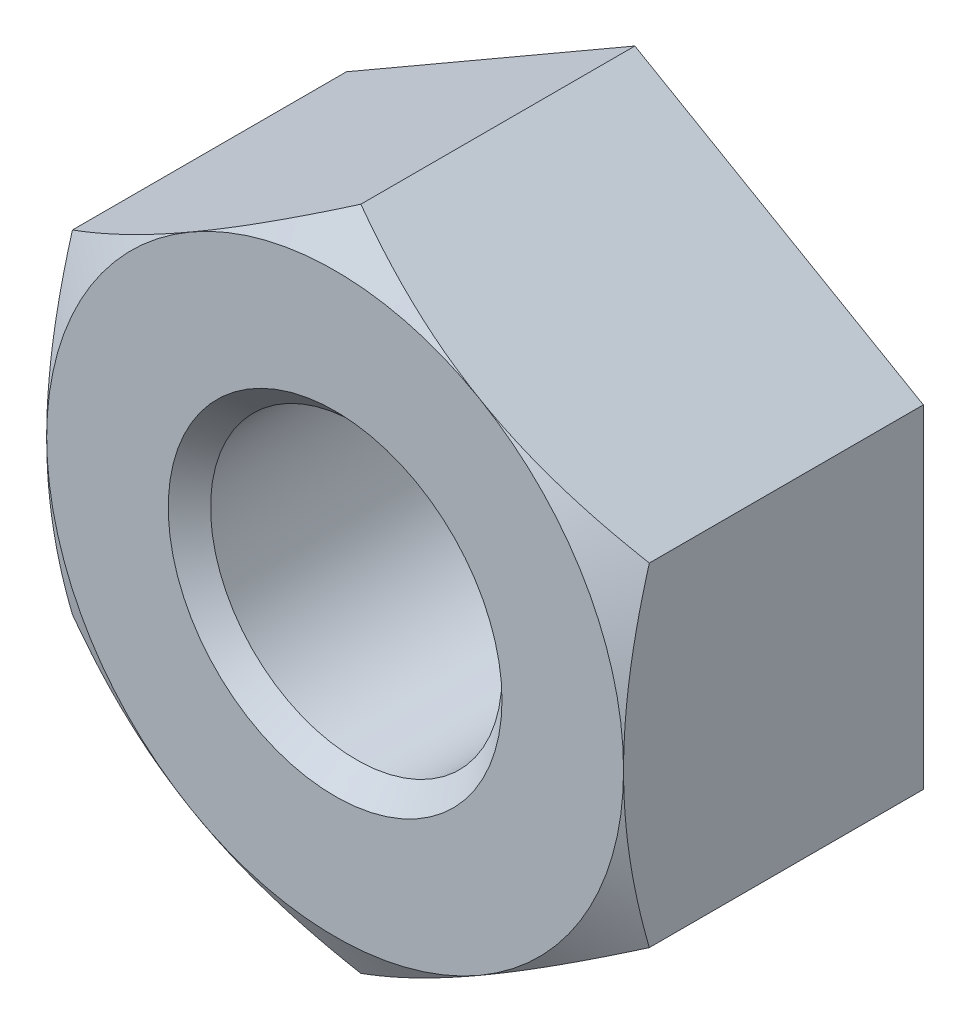
SolidWorks part; units mm, degrees
ref_plane "Front Plane" through (0, 0, 0) normal (0, 0, 1) x (1, 0, 0)
ref_plane "Top Plane" through (0, 0, 0) normal (0, 1, 0) x (1, 0, 0)
ref_plane "Right Plane" through (0, 0, 0) normal (1, 0, 0) x (0, 0, -1)
sketch "Sketch1" plane through (0, 0, 0) normal (0, 0, 1) x (1, 0, 0)
  line L1 (20.7846, -12) -> (20.7846, 12)
  line L2 (20.7846, 12) -> (0, 24)
  line L3 (0, 24) -> (-20.7846, 12)
  line L4 (-20.7846, 12) -> (-20.7846, -12)
  line L5 (-20.7846, -12) -> (0, -24)
  line L6 (0, -24) -> (20.7846, -12)
  circle A0 centre (0, 0) radius 20.7846 construction
extrude "Boss-Extrude1" add sketch "Sketch1" along normal blind 21.6
sketch "Sketch3" plane through (0, 0, 21.6) normal (0, 0, 1) x (1, 0, 0)
  circle A0 centre (0, 0) radius 20.7846
extrude "Cut-Extrude1" cut sketch "Sketch3" against normal blind 21.6 draft 60 flip side to cut
sketch "Sketch4" plane through (0, 0, 21.6) normal (0, 0, 1) x (1, 0, 0)
  point P0 (0, 0)
hole_wizard "M24 Tapped Hole1" positions "Sketch4" profile "Sketch5" tap size "M24" standard "ISO" end condition through all
sketch "Sketch5" plane through (0, 0, 21.6) normal (1, 0, 0) x (0, -1, 0)
  line L0 (0, 0) -> (0, 21.6)
  line L1 (0, 21.6) -> (10.5, 21.6)
  line L2 (10.5, 21.6) -> (10.5, 1.525)
  line L3 (10.5, 1.525) -> (12.025, 0)
  line L5 (12.025, 0) -> (0, 0)
  line L6 (-10.5, 1.525) -> (-12.025, 0) construction
  line L11 (0, -6.35) -> (0, 107.95) construction
  dimension "Thru Tap Drill Dia." = 21
  dimension "Thru Tap Drill Depth" = 21.6
  dimension "Near C'Sink Dia." = 24.05
  dimension "Near C'Sink Angle" = 90
cosmetic thread "Hole Thread1" parameters "D2"=24
